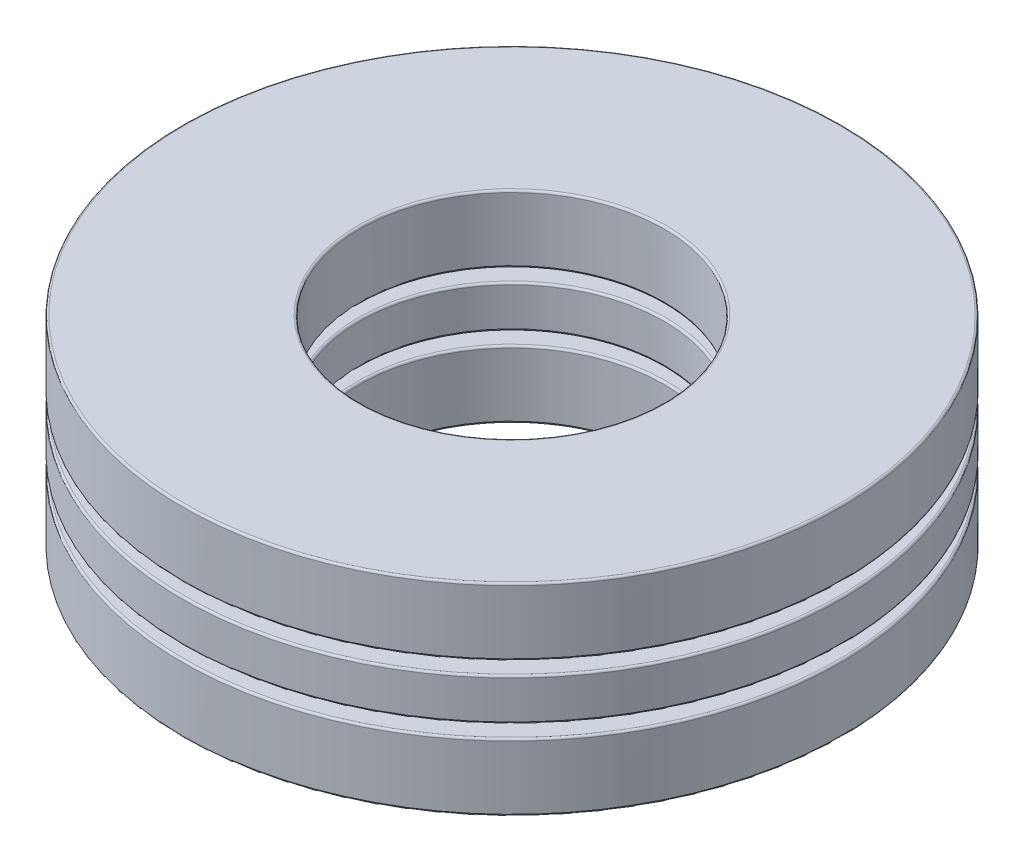
SolidWorks part; units mm, degrees
ref_plane "Front Plane" through (0, 0, 0) normal (0, 0, 1) x (1, 0, 0)
ref_plane "Top Plane" through (0, 0, 0) normal (0, 1, 0) x (1, 0, 0)
ref_plane "Right Plane" through (0, 0, 0) normal (1, 0, 0) x (0, 0, -1)
sketch "Sketch1" plane through (0, 0, 0) normal (1, 0, 0) x (0, 0, -1)
  line L0 (-10.3188, 0) -> (10.3187, 0) construction
  line L1 (0, -3.1623) -> (0, 3.1623) construction
  line L2 (-10.3188, 0.6588) -> (-4.7625, 0.6588)
  line L3 (-10.3188, 0.6588) -> (-10.3188, -0.6588)
  line L4 (-10.3188, -0.6588) -> (-4.7625, -0.6588)
  line L5 (-4.7625, 0.6588) -> (-4.7625, -0.6588)
  line L6 (-7.5406, 1.0541) -> (-7.5406, -1.0541) construction
  circle A0 centre (-7.5406, 0) radius 1.0541 construction
  point P13 (-7.5406, 0.6588)
  dimension "D1" = 2.1082
  dimension "OD" = 20.6375
  dimension "Shaft Dia" = 9.525
  dimension "Th" = 6.3246
  dimension "D2" = 1.3176
revolve "Revolve1" add sketch "Sketch1" angle 360 about L1
sketch "Sketch3" plane through (0, 0, 0) normal (1, 0, 0) x (0, 0, -1)
  line L0 (-7.5406, 1.0541) -> (-7.5406, -1.0541)
  arc A0 (-7.5406, 1.0541) -> (-7.5406, -1.0541) centre (-7.5406, 0) ccw
  circle A1 centre (-7.5406, 0) radius 1.0541 construction
revolve "Cut-Revolve1" cut sketch "Sketch3" angle 360 about L0
sketch "Sketch2" plane through (0, 0, 0) normal (1, 0, 0) x (0, 0, -1)
  line L0 (-7.5406, 1.0541) -> (-7.5406, -1.0541)
  arc A0 (-7.5406, 1.0541) -> (-7.5406, -1.0541) centre (-7.5406, 0) ccw
  circle A2 centre (-7.5406, 0) radius 1.0541 construction
revolve "Revolve2" add sketch "Sketch2" angle 360 about L0
ref_axis "Axis1" through (0, 3.1623, 0) along (0, -1, 0)
pattern_circular "CirPattern1" count 8 every 45 about axis through (0, 3.1623, 0) along (0, -1, 0) of bodies 187
pattern_circular "CirPattern2" count 8 every 45 about axis through (0, 0, 0) along (0, 1, 0) of "Cut-Revolve1"
sketch "Sketch4" plane through (0, 0, 0) normal (1, 0, 0) x (0, 0, -1)
  line L0 (-10.3188, 0.6588) -> (-10.3188, -0.6588) construction
  line L1 (-10.3188, 1.0541) -> (-4.7625, 1.0541)
  line L2 (-10.3188, 1.0541) -> (-10.3188, 3.1623)
  line L3 (-10.3188, 3.1623) -> (-4.7625, 3.1623)
  line L4 (-4.7625, 1.0541) -> (-4.7625, 3.1623)
  line L5 (-10.3188, -3.1623) -> (-4.7625, -3.1623)
  line L6 (-10.3188, -3.1623) -> (-10.3188, -1.0541)
  line L7 (-10.3188, -1.0541) -> (-4.7625, -1.0541)
  line L8 (-4.7625, -3.1623) -> (-4.7625, -1.0541)
  line L9 (-7.5406, 1.0541) -> (-7.5406, -1.0541) construction
  line L10 (-4.7625, 0.6588) -> (-4.7625, -0.6588) construction
  line L11 (0, 0) -> (-10.3188, 0) construction
  line L12 (-10.3188, 0) -> (10.3187, 0) construction
  dimension "Ht" = 6.3246
revolve "Revolve3" add sketch "Sketch4" angle 360 about L1
fillet "Fillet1" radius 0.0632 4 edges at (0, 1.0541, -4.7625) (0, 3.1623, -4.7625) (0, 1.0541, -10.3188) (0, 3.1623, -10.3188)
fillet "Fillet2" radius 0.0632 4 edges at (0, -0.6588, -4.7625) (0, 0.6588, -4.7625) (0, -0.6588, -10.3188) (0, 0.6588, -10.3188)
fillet "Fillet3" radius 0.0632 4 edges at (0, -3.1623, -4.7625) (0, -1.0541, -4.7625) (0, -3.1623, -10.3188) (0, -1.0541, -10.3188)
equation "\"D1@Sketch1\" = \"Th@Sketch1\"/3"
equation "\"D2@Sketch1\" = \"D1@Sketch1\"*.625"
equation "\"Balls@CirPattern1\" = \"OD@Sketch1\"*10"
equation "\"Angle@CirPattern1\" = 360/\"Balls@CirPattern1\""
equation "\"D1@CirPattern2\" = \"Balls@CirPattern1\""
equation "\"D2@CirPattern2\" = \"Angle@CirPattern1\""
equation "\"D1@Fillet1\" = \"Th@Sketch1\"*.01"
equation "\"D1@Fillet2\" = \"D1@Fillet1\""
equation "\"D1@Fillet3\" = \"D1@Fillet1\""
